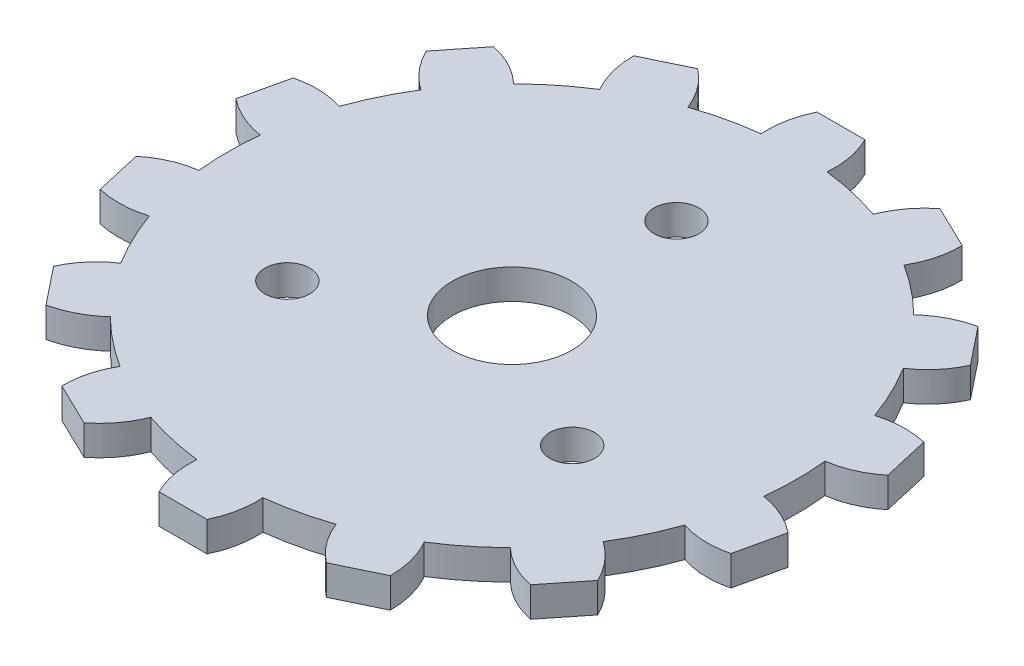
SolidWorks part; units mm, degrees
ref_plane "Front Plane" through (0, 0, 0) normal (0, 0, 1) x (1, 0, 0)
ref_plane "Top Plane" through (0, 0, 0) normal (0, 1, 0) x (1, 0, 0)
ref_plane "Right Plane" through (0, 0, 0) normal (1, 0, 0) x (0, 0, -1)
sketch "Sketch1" plane through (0, 0, 0) normal (0, 1, 0) x (1, 0, 0)
  line L1 (0, 22) -> (-1.6, 22)
  line L2 (0, 22) -> (1.6, 22)
  line L3 (9.5454, 19.8213) -> (8.1039, 20.5155)
  line L4 (9.5454, 19.8213) -> (10.987, 19.1271)
  line L5 (17.2003, 13.7168) -> (16.2027, 14.9677)
  line L6 (17.2003, 13.7168) -> (18.1979, 12.4658)
  line L7 (21.4484, 4.8955) -> (21.0924, 6.4553)
  line L8 (21.4484, 4.8955) -> (21.8044, 3.3356)
  line L9 (21.4484, -4.8955) -> (21.8044, -3.3356)
  line L10 (21.4484, -4.8955) -> (21.0924, -6.4553)
  line L11 (17.2003, -13.7168) -> (18.1979, -12.4658)
  line L12 (17.2003, -13.7168) -> (16.2027, -14.9677)
  line L13 (9.5454, -19.8213) -> (10.987, -19.1271)
  line L14 (9.5454, -19.8213) -> (8.1039, -20.5155)
  line L15 (0, -22) -> (1.6, -22)
  line L16 (0, -22) -> (-1.6, -22)
  line L17 (-9.5454, -19.8213) -> (-8.1039, -20.5155)
  line L18 (-9.5454, -19.8213) -> (-10.987, -19.1271)
  line L19 (-17.2003, -13.7168) -> (-16.2027, -14.9677)
  line L20 (-17.2003, -13.7168) -> (-18.1979, -12.4658)
  line L21 (-21.4484, -4.8955) -> (-21.0924, -6.4553)
  line L22 (-21.4484, -4.8955) -> (-21.8044, -3.3356)
  line L23 (-21.4484, 4.8955) -> (-21.8044, 3.3356)
  line L24 (-21.4484, 4.8955) -> (-21.0924, 6.4553)
  line L25 (-17.2003, 13.7168) -> (-18.1979, 12.4658)
  line L26 (-17.2003, 13.7168) -> (-16.2027, 14.9677)
  line L27 (-9.5454, 19.8213) -> (-10.987, 19.1271)
  line L28 (-9.5454, 19.8213) -> (-8.1039, 20.5155)
  arc A1 (2.206, -18.8715) -> (6.2005, -17.9598) centre (0, 0) ccw
  circle A2 centre (0, 0) radius 4
  circle A17 centre (0, 11) radius 1.5
  circle A18 centre (9.5263, -5.5) radius 1.5
  circle A19 centre (-9.5263, -5.5) radius 1.5
  arc A20 (10.1755, -16.0455) -> (13.379, -13.4909) centre (0, 0) ccw
  arc A21 (16.1297, -10.0415) -> (17.9075, -6.3499) centre (0, 0) ccw
  arc A22 (18.8892, -2.0487) -> (18.8892, 2.0487) centre (0, 0) ccw
  arc A23 (17.9075, 6.3499) -> (16.1297, 10.0415) centre (0, 0) ccw
  arc A24 (13.379, 13.4909) -> (10.1755, 16.0455) centre (0, 0) ccw
  arc A25 (6.2005, 17.9598) -> (2.206, 18.8715) centre (0, 0) ccw
  arc A26 (-2.206, 18.8715) -> (-6.2005, 17.9598) centre (0, 0) ccw
  arc A27 (-16.1297, 10.0415) -> (-17.9075, 6.3499) centre (0, 0) ccw
  arc A28 (-10.1755, 16.0455) -> (-13.379, 13.4909) centre (0, 0) ccw
  arc A29 (-18.8892, 2.0487) -> (-18.8892, -2.0487) centre (0, 0) ccw
  arc A30 (-17.9075, -6.3499) -> (-16.1297, -10.0415) centre (0, 0) ccw
  arc A31 (-13.379, -13.4909) -> (-10.1755, -16.0455) centre (0, 0) ccw
  arc A32 (-6.2005, -17.9598) -> (-2.206, -18.8715) centre (0, 0) ccw
  spline S0 degree 2 poles (-1.6, 22) (-2.3181, 20.5095) (-2.206, 18.8715) knots 0 0 0 1 1 1
  spline S1 degree 2 poles (1.6, 22) (2.3475, 20.5141) (2.206, 18.8715) knots 0 0 0 1 1 1
  spline S2 degree 2 poles (8.1039, 20.5155) (6.8102, 19.4842) (6.2005, 17.9598) knots 0 0 0 1 1 1
  spline S3 degree 2 poles (10.987, 19.1271) (11.0157, 17.464) (10.1755, 16.0455) knots 0 0 0 1 1 1
  spline S4 degree 2 poles (16.2027, 14.9677) (14.5896, 14.5999) (13.379, 13.4909) knots 0 0 0 1 1 1
  spline S5 degree 2 poles (18.1979, 12.4658) (17.5022, 10.955) (16.1297, 10.0415) knots 0 0 0 1 1 1
  spline S6 degree 2 poles (21.0924, 6.4553) (19.4794, 6.8238) (17.9075, 6.3499) knots 0 0 0 1 1 1
  spline S7 degree 2 poles (21.8044, 3.3356) (20.5221, 2.2762) (18.8892, 2.0487) knots 0 0 0 1 1 1
  spline S8 degree 2 poles (21.8044, -3.3356) (20.5111, -2.3038) (18.8892, -2.0487) knots 0 0 0 1 1 1
  spline S9 degree 2 poles (21.0924, -6.4553) (19.4774, -6.8534) (17.9075, -6.3499) knots 0 0 0 1 1 1
  spline S10 degree 2 poles (18.1979, -12.4658) (17.4803, -10.9751) (16.1297, -10.0415) knots 0 0 0 1 1 1
  spline S11 degree 2 poles (16.2027, -14.9677) (14.575, -14.6257) (13.379, -13.4909) knots 0 0 0 1 1 1
  spline S12 degree 2 poles (10.987, -19.1271) (10.9873, -17.4726) (10.1755, -16.0455) knots 0 0 0 1 1 1
  spline S13 degree 2 poles (8.1039, -20.5155) (6.7857, -19.5011) (6.2005, -17.9598) knots 0 0 0 1 1 1
  spline S14 degree 2 poles (1.6, -22) (2.3181, -20.5095) (2.206, -18.8715) knots 0 0 0 1 1 1
  spline S15 degree 2 poles (-1.6, -22) (-2.3475, -20.5141) (-2.206, -18.8715) knots 0 0 0 1 1 1
  spline S16 degree 2 poles (-8.1039, -20.5155) (-6.8102, -19.4842) (-6.2005, -17.9598) knots 0 0 0 1 1 1
  spline S17 degree 2 poles (-10.987, -19.1271) (-11.0157, -17.464) (-10.1755, -16.0455) knots 0 0 0 1 1 1
  spline S18 degree 2 poles (-16.2027, -14.9677) (-14.5896, -14.5999) (-13.379, -13.4909) knots 0 0 0 1 1 1
  spline S19 degree 2 poles (-18.1979, -12.4658) (-17.5022, -10.955) (-16.1297, -10.0415) knots 0 0 0 1 1 1
  spline S20 degree 2 poles (-21.0924, -6.4553) (-19.4794, -6.8238) (-17.9075, -6.3499) knots 0 0 0 1 1 1
  spline S21 degree 2 poles (-21.8044, -3.3356) (-20.5221, -2.2762) (-18.8892, -2.0487) knots 0 0 0 1 1 1
  spline S22 degree 2 poles (-21.8044, 3.3356) (-20.5111, 2.3038) (-18.8892, 2.0487) knots 0 0 0 1 1 1
  spline S23 degree 2 poles (-21.0924, 6.4553) (-19.4774, 6.8534) (-17.9075, 6.3499) knots 0 0 0 1 1 1
  spline S24 degree 2 poles (-18.1979, 12.4658) (-17.4803, 10.9751) (-16.1297, 10.0415) knots 0 0 0 1 1 1
  spline S25 degree 2 poles (-16.2027, 14.9677) (-14.575, 14.6257) (-13.379, 13.4909) knots 0 0 0 1 1 1
  spline S26 degree 2 poles (-10.987, 19.1271) (-10.9873, 17.4726) (-10.1755, 16.0455) knots 0 0 0 1 1 1
  spline S27 degree 2 poles (-8.1039, 20.5155) (-6.7857, 19.5011) (-6.2005, 17.9598) knots 0 0 0 1 1 1
  point P107 (0, 0)
  point P113 (0, 0)
  dimension "D1" = 3
  dimension "D2" = 38
  dimension "D5" = 8
  dimension "D3" = 1.6
  dimension "D4" = 1.6
  dimension "D8" = 11
  dimension "D6" = 14
  dimension "D7" = 3
extrude "Boss-Extrude1" add sketch "Sketch1" along normal blind 2
